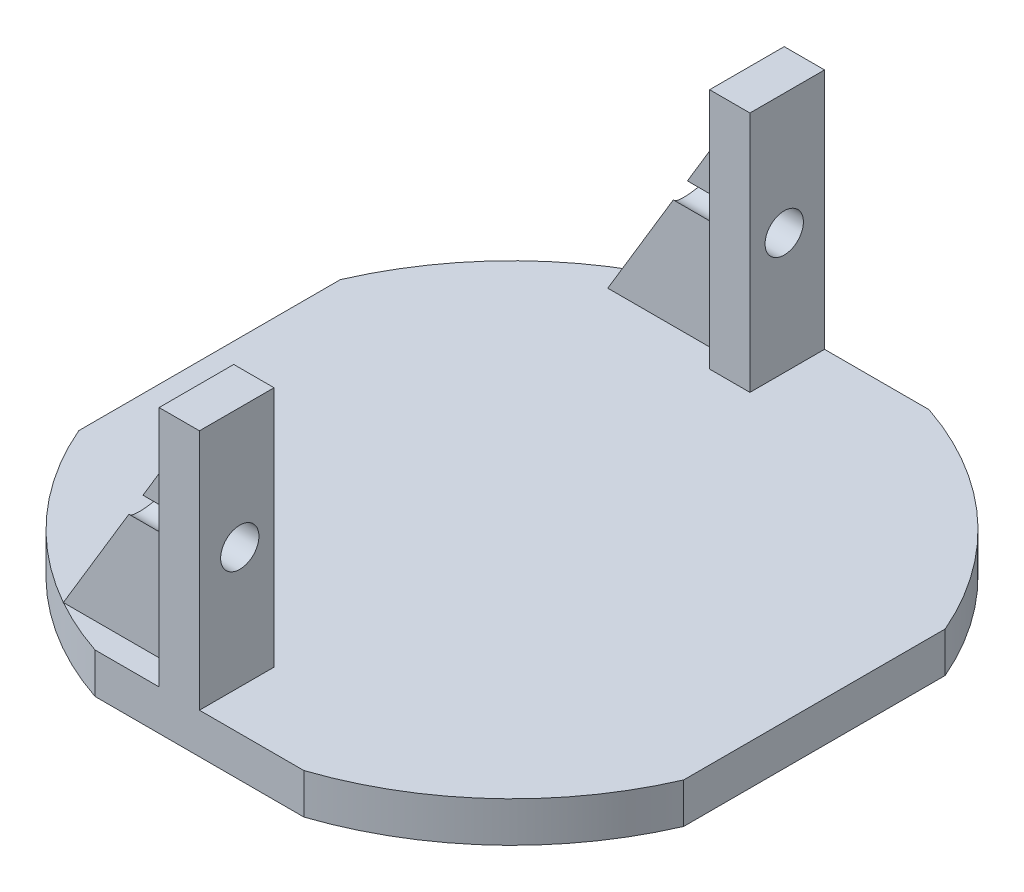
SolidWorks part; units mm, degrees
ref_plane "前视基准面" through (0, 0, 0) normal (0, 0, 1) x (1, 0, 0)
ref_plane "上视基准面" through (0, 0, 0) normal (0, 1, 0) x (1, 0, 0)
ref_plane "右视基准面" through (0, 0, 0) normal (1, 0, 0) x (0, 0, -1)
other "Configuration Table"
sketch "草图1" plane through (0, 0, 0) normal (0, 1, 0) x (1, 0, 0)
  circle A0 centre (0, 0) radius 4
  dimension "D1" = 8
extrude "拉伸-薄壁1" add sketch "草图1" along normal blind 5 thin
ref_plane "基准面1" through (6, 0, 0) normal (1, 0, 0) x (0, 0, -1)
sketch "草图2" plane through (6, 0, 0) normal (1, 0, 0) x (0, 0, -1)
  line L0 (0, 6.4337) -> (0, -1.8449)
  circle A0 centre (0, 2.6371) radius 1.45
  dimension "D1" = 2.9
extrude "切除-拉伸1" cut sketch "草图2" against normal up to next contours A0
sketch "草图3" plane through (0, 5, 0) normal (0, 1, 0) x (1, 0, 0)
  line L1 (-15, 15.5) -> (15, 15.5)
  line L2 (-15, 15.5) -> (-15, -15.5)
  line L3 (-15, -15.5) -> (15, -15.5)
  line L4 (15, 15.5) -> (15, -15.5)
  line L5 (-15, 15.5) -> (15, -15.5) construction
  line L6 (-15, -15.5) -> (15, 15.5) construction
  circle A1 centre (0, 0) radius 6
  circle A2 centre (0, 0) radius 6
  circle M6 centre (0, 0) radius 6
  dimension "D2" = 31
  dimension "D3" = 30
  dimension "D1" = 0
extrude "凸台-拉伸1" add sketch "草图3" along normal blind 2 contours L4 L1 L2 L3 M6 | A2
sketch "草图6" plane through (0, 7, 0) normal (0, 1, 0) x (1, 0, 0)
  line L0 (0, 16.5375) -> (0, -17.6622) construction
  line L1 (-17.8286, 0) -> (21.1047, 0) construction
  line L2 (-5, -11.5) -> (5, -11.5)
  line L3 (-5, -11.5) -> (-5, 11.5)
  line L4 (15, -15.5) -> (15, 15.5)
  line L5 (15, 15.5) -> (-15, 15.5)
  line L6 (-15, 15.5) -> (-15, -15.5)
  line L7 (-15, -15.5) -> (15, -15.5)
  line L8 (15, -15.5) -> (15, 15.5)
  line L9 (15, 15.5) -> (-15, 15.5)
  line L10 (-15, 15.5) -> (-15, -15.5)
  line L11 (-15, -15.5) -> (15, -15.5)
  line L12 (-5, 11.5) -> (5, 11.5)
  line L13 (5, -11.5) -> (5, 11.5)
  line L14 (-5, -11.5) -> (5, 11.5) construction
  line L15 (-5, 11.5) -> (5, -11.5) construction
  line L16 (0, -11.5) -> (-2, -11.5)
  line L17 (0, -11.5) -> (0, -15.5)
  line L18 (0, -15.5) -> (-2, -15.5)
  line L19 (-2, -11.5) -> (-2, -15.5)
  line L20 (0, 15.5) -> (-2, 15.5)
  line L21 (-2, 11.5) -> (-2, 15.5)
  line L22 (0, 11.5) -> (-2, 11.5)
  line L23 (0, 11.5) -> (0, 15.5)
  point P6 (0, 0)
  dimension "D2" = 15
  dimension "D3" = 23
  dimension "D4" = 10
  dimension "D5" = 2
  dimension "D1" = 0
extrude "凸台-拉伸2" add sketch "草图6" along normal blind 12 contours L12 L23 L9 L21 | L2 L19 L11 L17
sketch "草图7" plane through (-2, 0, 0) normal (-1, 0, 0) x (0, 0, 1)
  line L0 (-11.5, 7) -> (-15.5, 7) construction
  line L1 (-14.25, 17) -> (-12.75, 17)
  line L2 (-14.25, 17) -> (-14.25, 7)
  line L3 (-14.25, 7) -> (-12.75, 7)
  line L4 (-12.75, 17) -> (-12.75, 7)
  point P6 (-13.5, 7)
  dimension "D1" = 1.5
  dimension "D2" = 10
sketch "草图8" plane through (0, 7, 0) normal (0, 1, 0) x (1, 0, 0)
  line L0 (-2, 14.25) -> (-2, 12.75) construction
  line L1 (-2, 14.25) -> (-8, 14.25)
  line L2 (-2, 14.25) -> (-2, 12.75)
  line L3 (-2, 12.75) -> (-8, 12.75)
  line L4 (-8, 14.25) -> (-8, 12.75)
  line L5 (-2, 11.5) -> (-2, 15.5) construction
  point P6 (-2, 13.5)
  dimension "D1" = 6
  dimension "D2" = 1.5
ref_plane "基准面2" through (0, 0, -12.75) normal (0, 0, 1) x (1, 0, 0)
sketch "草图9" plane through (0, 0, -12.75) normal (0, 0, 1) x (1, 0, 0)
  line L0 (-2, 7) -> (-8, 7) construction
  line L1 (-2, 17) -> (-2, 7) construction
  line L2 (-2, 7) -> (-8, 7)
  line L3 (-2, 17) -> (-2, 7)
  line L4 (-2, 17) -> (-8, 7)
extrude "凸台-拉伸3" add sketch "草图9" against normal blind 1.5
ref_plane "基准面3" through (0, 0, 15.5) normal (0, 0, 1) x (1, 0, 0)
sketch "草图10" plane through (0, 0, 15.5) normal (0, 0, 1) x (1, 0, 0)
  line L3 (-2, 7) -> (-2, 17)
  line L4 (-2, 17) -> (-8, 7)
  line L5 (-8, 7) -> (-2, 7)
  line L6 (-2, 7) -> (-2, 17)
  line L7 (-2, 17) -> (-8, 7)
  line L8 (-8, 7) -> (-2, 7)
  dimension "D1" = 0
extrude "凸台-拉伸4" add sketch "草图10" against normal blind 1.5 from offset 1.25 offset against normal yes
sketch "草图11" plane through (0, 0, 0) normal (1, 0, 0) x (0, 0, -1)
  line L0 (-13.5, 21.8605) -> (-13.5, 2) construction
  line L1 (-20.4528, 13) -> (-6.5472, 13) construction
  line L4 (-15.5, 7) -> (-11.5, 7)
  line L5 (-11.5, 7) -> (-11.5, 19)
  line L6 (-11.5, 19) -> (-15.5, 19)
  line L7 (-15.5, 19) -> (-15.5, 7)
  line L8 (-15.5, 7) -> (-11.5, 7)
  line L9 (-11.5, 7) -> (-11.5, 19)
  line L10 (-11.5, 19) -> (-15.5, 19)
  line L11 (-15.5, 19) -> (-15.5, 7)
  circle A0 centre (-13.5, 13) radius 0.95
  point P8 (-13.5, 13)
  point P9 (-13.5, 19)
  dimension "D4" = 1.9
  dimension "D2" = 6
  dimension "D3" = 2
  dimension "D1" = 0
extrude "切除-拉伸3" cut sketch "草图11" against normal up to next contours A0
sketch "草图12" plane through (0, 0, 0) normal (1, 0, 0) x (0, 0, -1)
  line L0 (11.5, 19) -> (15.5, 7) construction
  line L1 (11.5, 7) -> (15.5, 19) construction
  line L4 (11.5, 7) -> (15.5, 7)
  line L5 (15.5, 7) -> (15.5, 19)
  line L6 (15.5, 19) -> (11.5, 19)
  line L7 (11.5, 19) -> (11.5, 7)
  line L8 (11.5, 7) -> (15.5, 7)
  line L9 (15.5, 7) -> (15.5, 19)
  line L10 (15.5, 19) -> (11.5, 19)
  line L11 (11.5, 19) -> (11.5, 7)
  circle A0 centre (13.5, 13) radius 0.95
  dimension "D2" = 1.9
  dimension "D1" = 0
extrude "切除-拉伸4" cut sketch "草图12" against normal up to next contours A0
sketch "草图13" plane through (0, 7, 0) normal (0, 1, 0) x (1, 0, 0)
  line L20 (-8, -14.25) -> (-8, -12.75)
  line L21 (-8, -12.75) -> (-2, -12.75)
  line L22 (-2, -12.75) -> (-2, -11.5)
  line L23 (-2, -11.5) -> (0, -11.5)
  line L24 (0, -11.5) -> (0, -15.5)
  line L25 (0, -15.5) -> (15, -15.5)
  line L26 (15, -15.5) -> (15, 15.5)
  line L27 (15, 15.5) -> (0, 15.5)
  line L28 (0, 15.5) -> (0, 11.5)
  line L29 (0, 11.5) -> (-2, 11.5)
  line L30 (-2, 11.5) -> (-2, 12.75)
  line L31 (-2, 12.75) -> (-8, 12.75)
  line L32 (-8, 12.75) -> (-8, 14.25)
  line L33 (-8, 14.25) -> (-2, 14.25)
  line L34 (-2, 14.25) -> (-2, 15.5)
  line L35 (-2, 15.5) -> (-15, 15.5)
  line L36 (-15, 15.5) -> (-15, -15.5)
  line L37 (-15, -15.5) -> (-2, -15.5)
  line L38 (-2, -15.5) -> (-2, -14.25)
  line L39 (-2, -14.25) -> (-8, -14.25)
  line L40 (-8, -14.25) -> (-8, -12.75)
  line L41 (-8, -12.75) -> (-2, -12.75)
  line L42 (-2, -12.75) -> (-2, -11.5)
  line L43 (-2, -11.5) -> (0, -11.5)
  line L44 (0, -11.5) -> (0, -15.5)
  line L45 (0, -15.5) -> (15, -15.5)
  line L46 (15, -15.5) -> (15, 15.5)
  line L47 (15, 15.5) -> (0, 15.5)
  line L48 (0, 15.5) -> (0, 11.5)
  line L49 (0, 11.5) -> (-2, 11.5)
  line L50 (-2, 11.5) -> (-2, 12.75)
  line L51 (-2, 12.75) -> (-8, 12.75)
  line L52 (-8, 12.75) -> (-8, 14.25)
  line L53 (-8, 14.25) -> (-2, 14.25)
  line L54 (-2, 14.25) -> (-2, 15.5)
  line L55 (-2, 15.5) -> (-15, 15.5)
  line L56 (-15, 15.5) -> (-15, -15.5)
  line L57 (-15, -15.5) -> (-2, -15.5)
  line L58 (-2, -15.5) -> (-2, -14.25)
  line L59 (-2, -14.25) -> (-8, -14.25)
  circle A0 centre (0, 0) radius 16.342
  line M28 (15, -15.5) -> (15, 15.5)
  line M29 (15, 15.5) -> (0, 15.5)
  line M38 (-15, 15.5) -> (-15, -15.5)
  line M39 (-15, -15.5) -> (-2, -15.5)
  dimension "D1" = 0
extrude "切除-拉伸5" cut sketch "草图13" against normal up to next contours A0 M38 M39 | A0 L45 M28 | A0 M28 M29 | A0 L55 M38
sketch "草图14" plane through (0, 0, 11.5) normal (0, 0, -1) x (-1, 0, 0)
  line L4 (0, 7) -> (2, 7)
  line L5 (2, 7) -> (2, 19)
  line L6 (2, 19) -> (0, 19)
  line L7 (0, 19) -> (0, 7)
  line L8 (0, 7) -> (2, 7)
  line L9 (2, 7) -> (2, 19)
  line L10 (2, 19) -> (0, 19)
  line L11 (0, 19) -> (0, 7)
  dimension "D1" = 0
extrude "切除-拉伸6" cut sketch "草图14" against normal blind 0.3
sketch "草图15" plane through (0, 0, -11.5) normal (0, 0, 1) x (1, 0, 0)
  line L4 (-2, 7) -> (0, 7)
  line L5 (0, 7) -> (0, 19)
  line L6 (0, 19) -> (-2, 19)
  line L7 (-2, 19) -> (-2, 7)
  line L8 (-2, 7) -> (0, 7)
  line L9 (0, 7) -> (0, 19)
  line L10 (0, 19) -> (-2, 19)
  line L11 (-2, 19) -> (-2, 7)
  dimension "D1" = 0
extrude "切除-拉伸7" cut sketch "草图15" against normal blind 0.3
